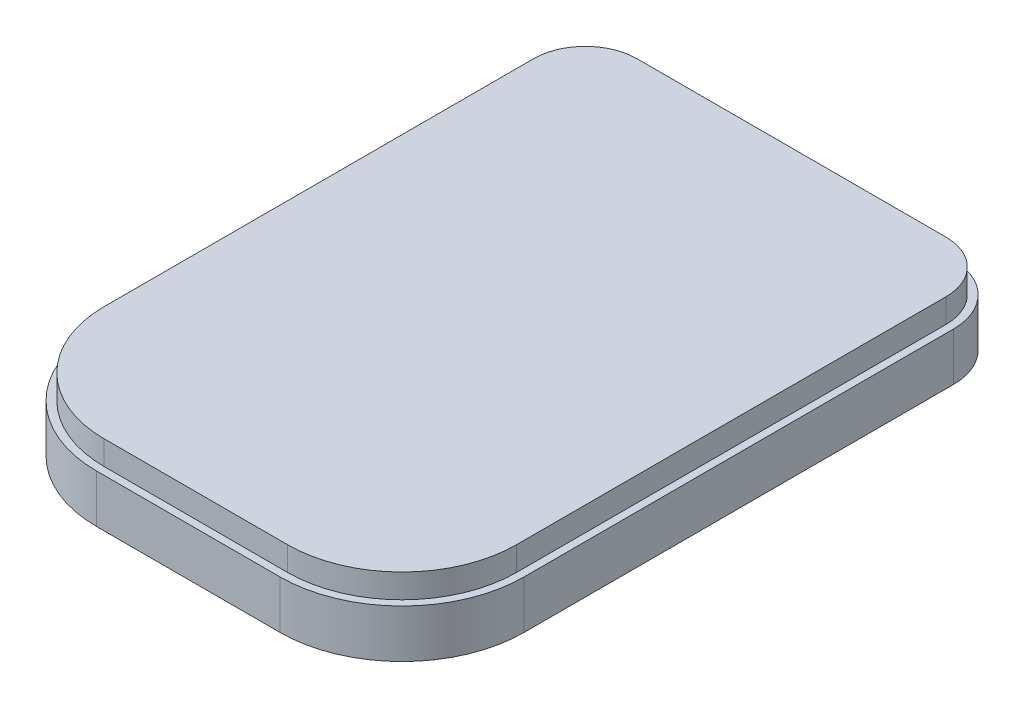
SolidWorks part; units mm, degrees
material "Mahogany"
ref_plane "Front Plane" through (0, 0, 0) normal (0, 0, 1) x (1, 0, 0)
ref_plane "Top Plane" through (0, 0, 0) normal (0, 1, 0) x (1, 0, 0)
ref_plane "Right Plane" through (0, 0, 0) normal (1, 0, 0) x (0, 0, -1)
sketch "Sketch1" plane through (0, 0, 0) normal (0, 1, 0) x (1, 0, 0)
  line L0 (32.1126, 63.5) -> (-32.1126, 63.5) construction
  line L1 (44.45, 51.1626) -> (44.45, -38.1) construction
  line L2 (-19.05, -63.5) -> (19.05, -63.5) construction
  line L3 (-44.45, 51.1626) -> (-44.45, -38.1) construction
  line L4 (32.1126, 63.5) -> (-32.1126, 63.5)
  line L5 (44.45, 51.1626) -> (44.45, -38.1)
  line L6 (-19.05, -63.5) -> (19.05, -63.5)
  line L7 (-44.45, 51.1626) -> (-44.45, -38.1)
  arc A0 (44.45, 51.1626) -> (32.1126, 63.5) centre (32.1126, 51.1626) ccw construction
  arc A1 (19.05, -63.5) -> (44.45, -38.1) centre (19.05, -38.1) ccw construction
  arc A2 (-44.45, -38.1) -> (-19.05, -63.5) centre (-19.05, -38.1) ccw construction
  arc A3 (-32.1126, 63.5) -> (-44.45, 51.1626) centre (-32.1126, 51.1626) ccw construction
  arc A4 (44.45, 51.1626) -> (32.1126, 63.5) centre (32.1126, 51.1626) ccw
  arc A5 (19.05, -63.5) -> (44.45, -38.1) centre (19.05, -38.1) ccw
  arc A6 (-44.45, -38.1) -> (-19.05, -63.5) centre (-19.05, -38.1) ccw
  arc A7 (-32.1126, 63.5) -> (-44.45, 51.1626) centre (-32.1126, 51.1626) ccw
extrude "Boss-Extrude1" add sketch "Sketch1" along normal blind 10
sketch "Sketch2" plane through (0, 10, 0) normal (0, 1, 0) x (1, 0, 0)
  line L0 (-42.8625, 51.1626) -> (-42.8625, -38.1)
  line L1 (-19.05, -61.9125) -> (19.05, -61.9125)
  line L2 (42.8625, -38.1) -> (42.8625, 51.1626)
  line L3 (32.1126, 61.9125) -> (-32.1126, 61.9125)
  line L4 (32.1126, 63.5) -> (-32.1126, 63.5)
  line L5 (-44.45, 51.1626) -> (-44.45, -38.1)
  line L6 (-19.05, -63.5) -> (19.05, -63.5)
  line L7 (44.45, -38.1) -> (44.45, 51.1626)
  line L8 (32.1126, 63.5) -> (-32.1126, 63.5) construction
  line L9 (-44.45, 51.1626) -> (-44.45, -38.1) construction
  line L10 (-19.05, -63.5) -> (19.05, -63.5) construction
  line L11 (44.45, -38.1) -> (44.45, 51.1626) construction
  arc A0 (-42.8625, -38.1) -> (-19.05, -61.9125) centre (-19.05, -38.1) ccw
  arc A1 (19.05, -61.9125) -> (42.8625, -38.1) centre (19.05, -38.1) ccw
  arc A2 (42.8625, 51.1626) -> (32.1126, 61.9125) centre (32.1126, 51.1626) ccw
  arc A3 (-32.1126, 61.9125) -> (-42.8625, 51.1626) centre (-32.1126, 51.1626) ccw
  arc A4 (44.45, 51.1626) -> (32.1126, 63.5) centre (32.1126, 51.1626) ccw
  arc A5 (-32.1126, 63.5) -> (-44.45, 51.1626) centre (-32.1126, 51.1626) ccw
  arc A6 (-44.45, -38.1) -> (-19.05, -63.5) centre (-19.05, -38.1) ccw
  arc A7 (19.05, -63.5) -> (44.45, -38.1) centre (19.05, -38.1) ccw
  arc A8 (44.45, 51.1626) -> (32.1126, 63.5) centre (32.1126, 51.1626) ccw construction
  arc A9 (-32.1126, 63.5) -> (-44.45, 51.1626) centre (-32.1126, 51.1626) ccw construction
  arc A10 (-44.45, -38.1) -> (-19.05, -63.5) centre (-19.05, -38.1) ccw construction
  arc A11 (19.05, -63.5) -> (44.45, -38.1) centre (19.05, -38.1) ccw construction
  dimension "D1" = 0
  dimension "D2" = 1.5875
extrude "Boss-Extrude2" add sketch "Sketch2" along normal blind 5
